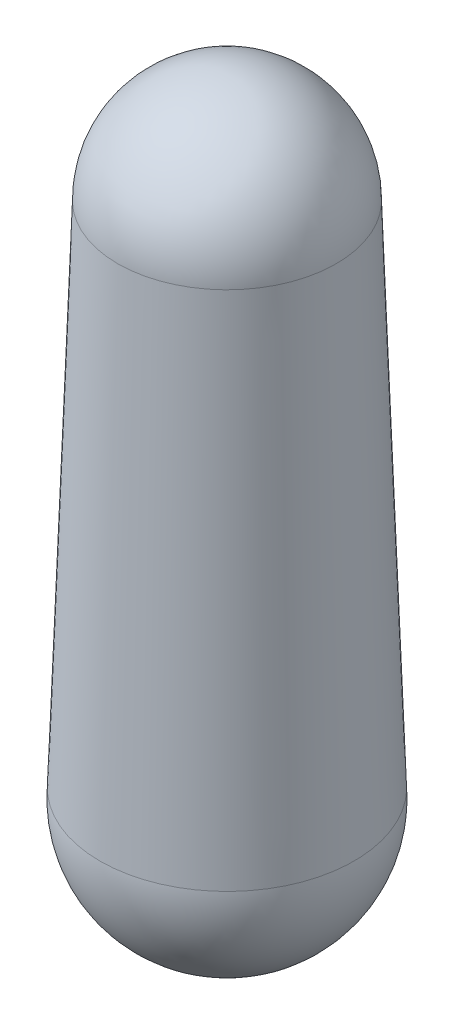
SolidWorks part; units mm, degrees
material "1060 Alloy"
ref_plane "Front Plane" through (0, 0, 0) normal (0, 0, 1) x (1, 0, 0)
ref_plane "Top Plane" through (0, 0, 0) normal (0, 1, 0) x (1, 0, 0)
ref_plane "Right Plane" through (0, 0, 0) normal (1, 0, 0) x (0, 0, -1)
sketch "Sketch1" plane through (0, 0, 0) normal (0, 1, 0) x (1, 0, 0)
  line L0 (0, 1.97) -> (0, -1.97) construction
  line L1 (0, 1.97) -> (0, -1.97)
  arc A0 (0, -1.97) -> (0, 1.97) centre (0, 0) ccw
  dimension "D1" = 3.94
revolve "Revolve1" add sketch "Sketch1" angle 360 about L0
sketch "Sketch2" plane through (0, 0, 0) normal (0, 1, 0) x (1, 0, 0)
  circle A0 centre (0, 0) radius 1.97
  circle A1 centre (0, 0) radius 1.97 construction
extrude "Boss-Extrude1" add sketch "Sketch2" along normal blind 8 draft 2
sketch "Sketch3" plane through (0, 8, 0) normal (0, 1, 0) x (1, 0, 0)
  line L0 (0, 1.6906) -> (0, -1.6906) construction
  line L1 (0, 1.6906) -> (0, -1.6906)
  arc A0 (0, -1.6906) -> (0, 1.6906) centre (0, 0) ccw
  circle A1 centre (0, 0) radius 1.6906 construction
  dimension "D1" = 1.6906
revolve "Revolve2" add sketch "Sketch3" angle 360 about L0
